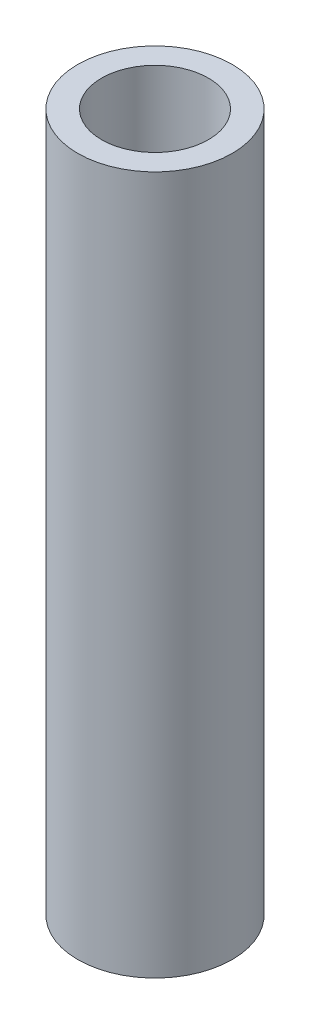
SolidWorks part; units mm, degrees
ref_plane "Front Plane" through (0, 0, 0) normal (0, 0, 1) x (1, 0, 0)
ref_plane "Top Plane" through (0, 0, 0) normal (0, 1, 0) x (1, 0, 0)
ref_plane "Right Plane" through (0, 0, 0) normal (1, 0, 0) x (0, 0, -1)
sketch "Sketch1" plane through (0, 0, 0) normal (0, 1, 0) x (1, 0, 0)
  circle A0 centre (0, 0) radius 2.857
  circle A1 centre (0, 0) radius 4.127
  dimension "D1" = 5.714
  dimension "D2" = 1.27
extrude "Boss-Extrude1" add sketch "Sketch1" along normal blind 37.338
